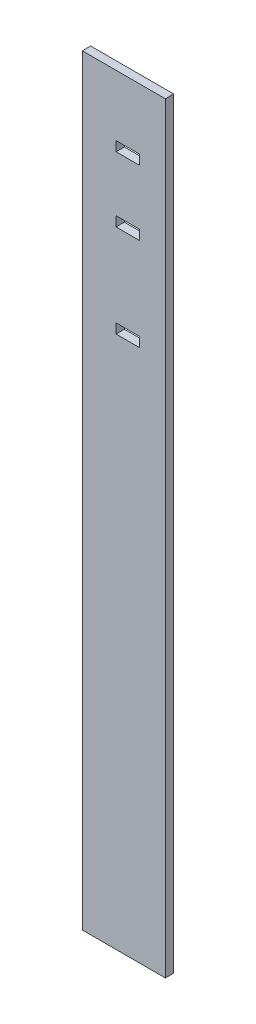
SolidWorks part; units mm, degrees
material "Balsa"
ref_plane "Front Plane" through (0, 0, 0) normal (1, 0, 0) x (0, 1, 0)
ref_plane "Top Plane" through (0, 0, 0) normal (0, 0, 1) x (0, 1, 0)
ref_plane "Right Plane" through (0, 0, 0) normal (0, 1, 0) x (-1, 0, 0)
sketch "Sketch1" plane through (0, 0, 0) normal (0, 0, 1) x (0, 1, 0)
  line L1 (-137.5, -15) -> (137.5, -15)
  line L2 (-137.5, -15) -> (-137.5, 15)
  line L3 (-137.5, 15) -> (137.5, 15)
  line L4 (137.5, -15) -> (137.5, 15)
  line L5 (-137.5, -15) -> (137.5, 15) construction
  line L6 (-137.5, 15) -> (137.5, -15) construction
  point P0 (0, 0)
  dimension "D1" = 275
  dimension "D2" = 30
extrude "Boss-Extrude1" add sketch "Sketch1" along normal blind 3
sketch "Sketch2" plane through (0, 0, 0) normal (0, 0, -1) x (1, 0, 0)
  line L4 (5.6908, -115.5) -> (5.6908, -112)
  line L5 (5.6908, -112) -> (-2.8092, -112)
  line L6 (-2.8092, -115.5) -> (5.6908, -115.5)
  line L7 (-2.8092, -112) -> (-2.8092, -115.5)
  line L16 (-2.8092, -55) -> (-2.8092, -58.5)
  line L17 (-2.8092, -58.5) -> (5.6908, -58.5)
  line L18 (5.6908, -55) -> (-2.8092, -55)
  line L19 (5.6908, -58.5) -> (5.6908, -55)
  line L20 (5.6908, -88.5) -> (-2.8092, -88.5)
  line L21 (-2.8092, -88.5) -> (-2.8092, -92)
  line L22 (-2.8092, -92) -> (5.6908, -92)
  line L23 (5.6908, -92) -> (5.6908, -88.5)
  spline S2 degree 3 poles (2.0604, -31.8082) (1.4408, -31.7216) (0.8212, -31.8082) (0.2174, -32.0692) (-0.3637, -32.4957) (-0.9247, -33.0825) (-1.4674, -33.8277) (-1.9925, -34.7303) (-2.4993, -35.7889) (-2.9867, -37.0016) (-3.4532, -38.3661) (-3.8973, -39.8794) (-4.3173, -41.5382) (-4.7116, -43.3387) (-5.0788, -45.2768) (-5.4173, -47.3481) (-5.7258, -49.5478) (-6.0034, -51.8707) (-6.2489, -54.3115) (-6.4617, -56.8644) (-6.6414, -59.5236) (-6.7876, -62.2828) (-6.9003, -65.1355) (-6.9798, -68.0752) (-7.0264, -71.0949) (-7.041, -74.1876) (-7.0244, -77.3462) (-6.9777, -80.5631) (-6.9021, -83.8309) (-6.799, -87.142) (-6.6701, -90.4887) (-6.5169, -93.8631) (-6.3412, -97.2573) (-6.1447, -100.6635) (-5.9293, -104.0736) (-5.6969, -107.4798) (-5.4491, -110.874) (-5.188, -114.2483) (-4.9152, -117.5949) (-4.6325, -120.9059) (-4.3416, -124.1737) (-4.0442, -127.3905) (-3.7421, -130.5488) (-3.4366, -133.6414) (-3.1294, -136.6609) (-2.8221, -139.6003) (-2.516, -142.4528) (-2.2127, -145.2116) (-1.9136, -147.8704) (-1.6201, -150.4229) (-1.3337, -152.8631) (-1.0558, -155.1855) (-0.7876, -157.3845) (-0.5307, -159.4549) (-0.2862, -161.3921) (-0.0557, -163.1914) (0.1598, -164.8486) (0.3589, -166.3599) (0.5405, -167.7218) (0.7036, -168.931) (0.8468, -169.9849) (0.9704, -170.8804) (1.0705, -171.6171) (1.1546, -172.1891) (1.2023, -172.6048) (1.2539, -172.8436) (1.2493, -173.0886) (1.6322, -173.0886) (1.6276, -172.8436) (1.6792, -172.6048) (1.7269, -172.1891) (1.811, -171.6171) (1.9111, -170.8804) (2.0347, -169.9849) (2.178, -168.931) (2.341, -167.7218) (2.5227, -166.3599) (2.7218, -164.8486) (2.9372, -163.1914) (3.1678, -161.3921) (3.4122, -159.4549) (3.6691, -157.3845) (3.9373, -155.1855) (4.2153, -152.8631) (4.5017, -150.4229) (4.7951, -147.8704) (5.0942, -145.2116) (5.3975, -142.4528) (5.7036, -139.6003) (6.011, -136.6609) (6.3181, -133.6414) (6.6236, -130.5488) (6.9258, -127.3905) (7.2231, -124.1737) (7.514, -120.9059) (7.7967, -117.5949) (8.0695, -114.2483) (8.3306, -110.874) (8.5784, -107.4798) (8.8109, -104.0736) (9.0262, -100.6635) (9.2227, -97.2573) (9.3984, -93.8631) (9.5516, -90.4887) (9.6806, -87.142) (9.7836, -83.8309) (9.8592, -80.5631) (9.9059, -77.3462) (9.9225, -74.1876) (9.908, -71.0949) (9.8613, -68.0752) (9.7818, -65.1355) (9.6691, -62.2828) (9.5229, -59.5236) (9.3432, -56.8644) (9.1304, -54.3115) (8.8849, -51.8707) (8.6073, -49.5478) (8.2988, -47.3481) (7.9603, -45.2768) (7.5932, -43.3387) (7.1988, -41.5382) (6.7788, -39.8794) (6.3347, -38.3661) (5.8682, -37.0016) (5.3808, -35.7889) (4.874, -34.7303) (4.3489, -33.8277) (3.8062, -33.0825) (3.2452, -32.4957) (2.6641, -32.0692) (2.0604, -31.8082) (1.4408, -31.7216) (0.8212, -31.8082) knots -0.006773 -0.004321 -0.002106 0 0.002106 0.004321 0.006773 0.009557 0.012734 0.016343 0.020406 0.024934 0.029933 0.035402 0.041337 0.047732 0.054575 0.061857 0.069565 0.077682 0.086195 0.095084 0.104333 0.113922 0.123829 0.134035 0.144516 0.155249 0.16621 0.177376 0.18872 0.200217 0.21184 0.223563 0.235359 0.2472 0.259058 0.270907 0.282718 0.294465 0.306118 0.317651 0.329037 0.340249 0.35126 0.362045 0.372579 0.382836 0.392793 0.402425 0.411711 0.420628 0.429156 0.437273 0.444962 0.452203 0.458979 0.465275 0.471075 0.476366 0.481134 0.485369 0.48906 0.492198 0.494776 0.496788 0.498228 0.499094 0.499383 0.500617 0.500906 0.501772 0.503212 0.505224 0.507802 0.51094 0.514631 0.518866 0.523634 0.528925 0.534725 0.541021 0.547797 0.555038 0.562727 0.570844 0.579372 0.588289 0.597575 0.607207 0.617164 0.627421 0.637955 0.64874 0.659751 0.670963 0.682349 0.693882 0.705535 0.717282 0.729093 0.740942 0.7528 0.764641 0.776437 0.78816 0.799783 0.81128 0.822624 0.83379 0.844751 0.855484 0.865965 0.876171 0.886078 0.895667 0.904916 0.913805 0.922318 0.930435 0.938143 0.945425 0.952268 0.958663 0.964598 0.970067 0.975066 0.979594 0.983657 0.987266 0.990443 0.993227 0.995679 0.997894 1 1.002106 1.004321 1.006773 only from (1.4408, -31.75) to (1.4408, -31.75)
  spline S4 degree 3 poles (2.0604, -31.8082) (1.4408, -31.7216) (0.8212, -31.8082) (0.2174, -32.0692) (-0.3637, -32.4957) (-0.9247, -33.0825) (-1.4674, -33.8277) (-1.9925, -34.7303) (-2.4993, -35.7889) (-2.9867, -37.0016) (-3.4532, -38.3661) (-3.8973, -39.8794) (-4.3173, -41.5382) (-4.7116, -43.3387) (-5.0788, -45.2768) (-5.4173, -47.3481) (-5.7258, -49.5478) (-6.0034, -51.8707) (-6.2489, -54.3115) (-6.4617, -56.8644) (-6.6414, -59.5236) (-6.7876, -62.2828) (-6.9003, -65.1355) (-6.9798, -68.0752) (-7.0264, -71.0949) (-7.041, -74.1876) (-7.0244, -77.3462) (-6.9777, -80.5631) (-6.9021, -83.8309) (-6.799, -87.142) (-6.6701, -90.4887) (-6.5169, -93.8631) (-6.3412, -97.2573) (-6.1447, -100.6635) (-5.9293, -104.0736) (-5.6969, -107.4798) (-5.4491, -110.874) (-5.188, -114.2483) (-4.9152, -117.5949) (-4.6325, -120.9059) (-4.3416, -124.1737) (-4.0442, -127.3905) (-3.7421, -130.5488) (-3.4366, -133.6414) (-3.1294, -136.6609) (-2.8221, -139.6003) (-2.516, -142.4528) (-2.2127, -145.2116) (-1.9136, -147.8704) (-1.6201, -150.4229) (-1.3337, -152.8631) (-1.0558, -155.1855) (-0.7876, -157.3845) (-0.5307, -159.4549) (-0.2862, -161.3921) (-0.0557, -163.1914) (0.1598, -164.8486) (0.3589, -166.3599) (0.5405, -167.7218) (0.7036, -168.931) (0.8468, -169.9849) (0.9704, -170.8804) (1.0705, -171.6171) (1.1546, -172.1891) (1.2023, -172.6048) (1.2539, -172.8436) (1.2493, -173.0886) (1.6322, -173.0886) (1.6276, -172.8436) (1.6792, -172.6048) (1.7269, -172.1891) (1.811, -171.6171) (1.9111, -170.8804) (2.0347, -169.9849) (2.178, -168.931) (2.341, -167.7218) (2.5227, -166.3599) (2.7218, -164.8486) (2.9372, -163.1914) (3.1678, -161.3921) (3.4122, -159.4549) (3.6691, -157.3845) (3.9373, -155.1855) (4.2153, -152.8631) (4.5017, -150.4229) (4.7951, -147.8704) (5.0942, -145.2116) (5.3975, -142.4528) (5.7036, -139.6003) (6.011, -136.6609) (6.3181, -133.6414) (6.6236, -130.5488) (6.9258, -127.3905) (7.2231, -124.1737) (7.514, -120.9059) (7.7967, -117.5949) (8.0695, -114.2483) (8.3306, -110.874) (8.5784, -107.4798) (8.8109, -104.0736) (9.0262, -100.6635) (9.2227, -97.2573) (9.3984, -93.8631) (9.5516, -90.4887) (9.6806, -87.142) (9.7836, -83.8309) (9.8592, -80.5631) (9.9059, -77.3462) (9.9225, -74.1876) (9.908, -71.0949) (9.8613, -68.0752) (9.7818, -65.1355) (9.6691, -62.2828) (9.5229, -59.5236) (9.3432, -56.8644) (9.1304, -54.3115) (8.8849, -51.8707) (8.6073, -49.5478) (8.2988, -47.3481) (7.9603, -45.2768) (7.5932, -43.3387) (7.1988, -41.5382) (6.7788, -39.8794) (6.3347, -38.3661) (5.8682, -37.0016) (5.3808, -35.7889) (4.874, -34.7303) (4.3489, -33.8277) (3.8062, -33.0825) (3.2452, -32.4957) (2.6641, -32.0692) (2.0604, -31.8082) (1.4408, -31.7216) (0.8212, -31.8082) knots -0.006773 -0.004321 -0.002106 0 0.002106 0.004321 0.006773 0.009557 0.012734 0.016343 0.020406 0.024934 0.029933 0.035402 0.041337 0.047732 0.054575 0.061857 0.069565 0.077682 0.086195 0.095084 0.104333 0.113922 0.123829 0.134035 0.144516 0.155249 0.16621 0.177376 0.18872 0.200217 0.21184 0.223563 0.235359 0.2472 0.259058 0.270907 0.282718 0.294465 0.306118 0.317651 0.329037 0.340249 0.35126 0.362045 0.372579 0.382836 0.392793 0.402425 0.411711 0.420628 0.429156 0.437273 0.444962 0.452203 0.458979 0.465275 0.471075 0.476366 0.481134 0.485369 0.48906 0.492198 0.494776 0.496788 0.498228 0.499094 0.499383 0.500617 0.500906 0.501772 0.503212 0.505224 0.507802 0.51094 0.514631 0.518866 0.523634 0.528925 0.534725 0.541021 0.547797 0.555038 0.562727 0.570844 0.579372 0.588289 0.597575 0.607207 0.617164 0.627421 0.637955 0.64874 0.659751 0.670963 0.682349 0.693882 0.705535 0.717282 0.729093 0.740942 0.7528 0.764641 0.776437 0.78816 0.799783 0.81128 0.822624 0.83379 0.844751 0.855484 0.865965 0.876171 0.886078 0.895667 0.904916 0.913805 0.922318 0.930435 0.938143 0.945425 0.952268 0.958663 0.964598 0.970067 0.975066 0.979594 0.983657 0.987266 0.990443 0.993227 0.995679 0.997894 1 1.002106 1.004321 1.006773 only from (1.4408, -31.75) to (1.4408, -31.75)
extrude "Cut-Extrude1" cut sketch "Sketch2" against normal through all contours L22 L23 L20 L21 | L5 L7 L6 L4 | L17 L19 L18 L16
